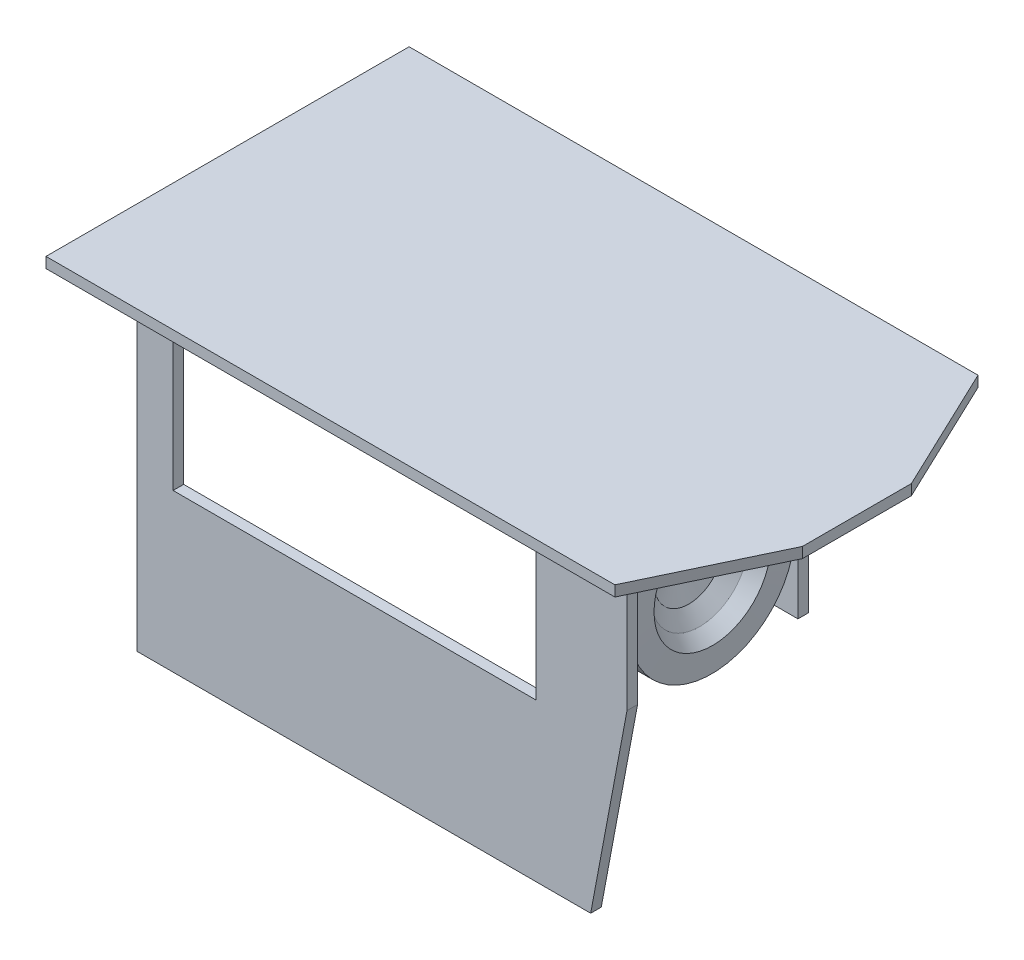
SolidWorks part; units mm, degrees
material "Nylon 101"
ref_plane "Alzado" through (0, 0, 0) normal (0, 0, 1) x (1, 0, 0)
ref_plane "Planta" through (0, 0, 0) normal (0, 1, 0) x (1, 0, 0)
ref_plane "Vista lateral" through (0, 0, 0) normal (1, 0, 0) x (0, 0, -1)
ref_plane "Plane1" through (0, 38.5, 0) normal (0, 1, 0) x (1, 0, 0)
sketch "Sketch1" plane through (0, 38.5, 0) normal (0, 1, 0) x (1, 0, 0)
  line L0 (-172, -60) -> (16, -60)
  line L1 (16, -60) -> (36, -18)
  line L2 (36, -18) -> (36, 18)
  line L3 (36, 18) -> (16, 60)
  line L4 (16, 60) -> (-172, 60)
  line L5 (-172, 60) -> (-172, -60)
extrude "Placa_superior_acromion" add sketch "Sketch1" along normal blind 3.5
ref_plane "Plane2" through (0, 0, 26.5) normal (0, 0, 1) x (1, 0, 0)
sketch "Sketch2" plane through (0, 0, 26.5) normal (0, 0, 1) x (1, 0, 0)
  line L0 (-172, 40) -> (-10, 40)
  line L1 (-10, 40) -> (-10, -22)
  line L2 (-10, -22) -> (-22, -86)
  line L3 (-22, -86) -> (-172, -86)
  line L4 (-172, -86) -> (-172, 40)
extrude "Placa_posterior_escapula" add sketch "Sketch2" along normal blind 3.5
ref_plane "Plane4" through (0, 0, -30) normal (0, 0, 1) x (1, 0, 0)
sketch "Sketch3" plane through (0, 0, -30) normal (0, 0, 1) x (1, 0, 0)
  line L0 (-150, 40) -> (-10, 40)
  line L1 (-10, 40) -> (-10, -24)
  line L2 (-10, -24) -> (-150, -24)
  line L3 (-150, -24) -> (-150, 40)
extrude "Placa_anterior" add sketch "Sketch3" along normal blind 3.5
ref_plane "Plane6" through (0, 0, -27) normal (0, 0, 1) x (1, 0, 0)
sketch "Sketch4" plane through (0, 0, -27) normal (0, 0, 1) x (1, 0, 0)
  line L0 (-36, 20) -> (-14, 20)
  line L1 (-14, 20) -> (-14, 40)
  line L2 (-14, 40) -> (-36, 40)
  line L3 (-36, 40) -> (-36, 20)
extrude "Cuello_glenoideo" add sketch "Sketch4" along normal blind 54
sketch "Sketch5" plane through (0, 0, 0) normal (0, 0, 1) x (1, 0, 0)
  line L0 (-36, 0) -> (-36, 27.5)
  line L1 (-36, 27.5) -> (-12, 27.5)
  line L2 (-12, 27.5) -> (-11.7748, 19.2902)
  line L3 (-11.7748, 19.2902) -> (-15.9806, 15.9806)
  line L4 (-15.9806, 15.9806) -> (-19.5722, 11.3)
  line L5 (-19.5722, 11.3) -> (-21.8299, 5.8493)
  line L6 (-21.8299, 5.8493) -> (-22.6, 0)
  line L7 (-22.6, 0) -> (-36, 0)
  line L8 (-40, 0) -> (-7.7748, 0) construction
revolve "Cavidad_glenoidea" add sketch "Sketch5" angle 360 about L8
ref_plane "Plane7" through (0, 0, 25) normal (0, 0, 1) x (1, 0, 0)
sketch "Sketch6" plane through (0, 0, 25) normal (0, 0, 1) x (1, 0, 0)
  line L0 (-160, -34) -> (-40, -34)
  line L1 (-40, -34) -> (-40, 22)
  line L2 (-40, 22) -> (-160, 22)
  line L3 (-160, 22) -> (-160, -34)
extrude "Ventana_posterior" cut sketch "Sketch6" along normal blind 6
ref_plane "Plane9" through (0, 0, -31) normal (0, 0, 1) x (1, 0, 0)
sketch "Sketch7" plane through (0, 0, -31) normal (0, 0, 1) x (1, 0, 0)
  line L0 (-140, -16) -> (-40, -16)
  line L1 (-40, -16) -> (-40, 10)
  line L2 (-40, 10) -> (-140, 10)
  line L3 (-140, 10) -> (-140, -16)
extrude "Ventana_anterior" cut sketch "Sketch7" along normal blind 6
